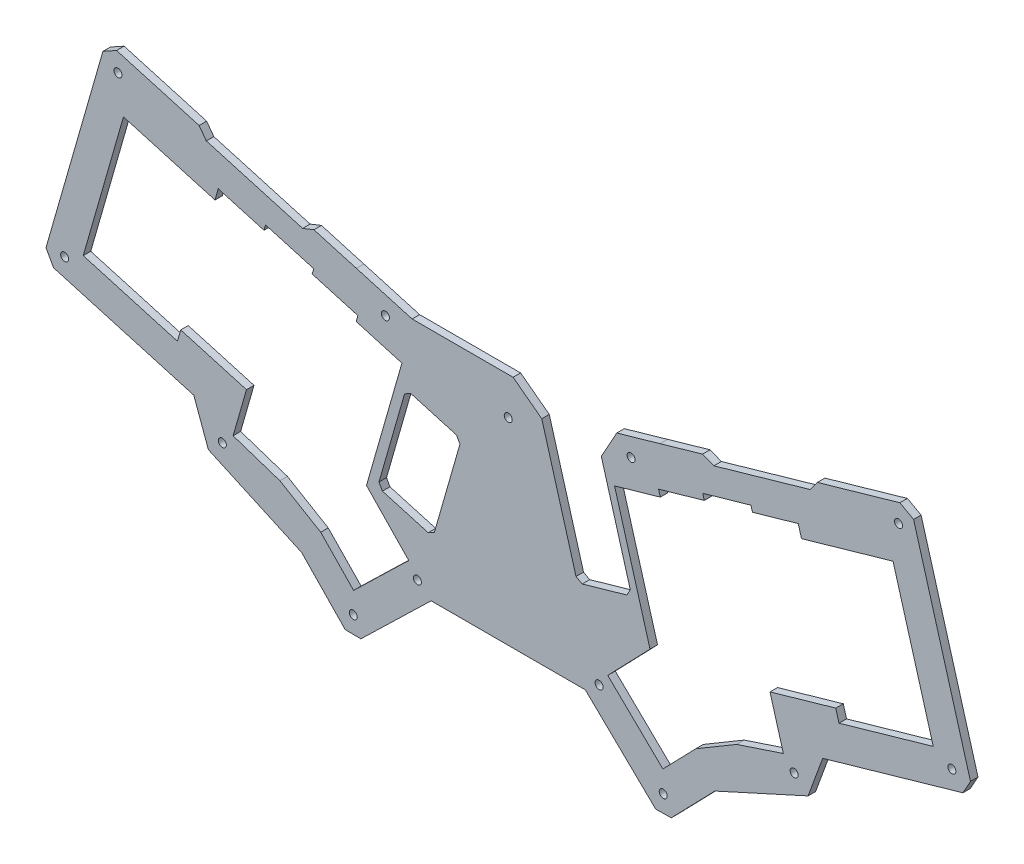
SolidWorks part; units mm, degrees
ref_plane "Plan de face" through (0, 0, 0) normal (0, 0, 1) x (1, 0, 0)
ref_plane "Plan de dessus" through (0, 0, 0) normal (0, 1, 0) x (1, 0, 0)
ref_plane "Plan de droite" through (0, 0, 0) normal (1, 0, 0) x (0, 0, -1)
sketch "Esquisse1" plane through (0, 0, 0) normal (0, 0, 1) x (1, 0, 0)
  line L0 (-121.6461, -32.0475) -> (-108.1875, -28.1884) construction
  line L1 (-108.1875, -28.1884) -> (-104.3283, -41.647) construction
  line L2 (-104.3283, -41.647) -> (-117.7869, -45.5062) construction
  line L3 (-117.7869, -45.5062) -> (-121.6461, -32.0475) construction
  line L4 (-100.1763, -37.9855) -> (-104.0355, -24.5269) construction
  line L5 (-104.0355, -24.5269) -> (-90.5769, -20.6677) construction
  line L6 (-90.5769, -20.6677) -> (-86.7177, -34.1263) construction
  line L7 (-86.7177, -34.1263) -> (-100.1763, -37.9855) construction
  line L8 (-82.5657, -30.4649) -> (-86.4249, -17.0063) construction
  line L9 (-86.4249, -17.0063) -> (-72.9663, -13.1471) construction
  line L10 (-72.9663, -13.1471) -> (-69.1071, -26.6057) construction
  line L11 (-69.1071, -26.6057) -> (-82.5657, -30.4649) construction
  line L12 (-63.6458, -27.5106) -> (-67.505, -14.0519) construction
  line L13 (-67.505, -14.0519) -> (-54.0463, -10.1927) construction
  line L14 (-54.0463, -10.1927) -> (-50.1872, -23.6514) construction
  line L15 (-50.1872, -23.6514) -> (-63.6458, -27.5106) construction
  line L16 (-44.0711, -26.8394) -> (-47.9303, -13.3808) construction
  line L17 (-47.9303, -13.3808) -> (-34.4717, -9.5216) construction
  line L18 (-34.4717, -9.5216) -> (-30.6125, -22.9802) construction
  line L19 (-30.6125, -22.9802) -> (-44.0711, -26.8394) construction
  line L20 (-25.8054, -21.6018) -> (-29.6646, -8.1432) construction
  line L21 (-29.6646, -8.1432) -> (-16.206, -4.284) construction
  line L22 (-16.206, -4.284) -> (-12.3468, -17.7426) construction
  line L23 (-12.3468, -17.7426) -> (-25.8054, -21.6018) construction
  line L24 (-116.4086, -50.3128) -> (-102.95, -46.4536) construction
  line L25 (-102.95, -46.4536) -> (-99.0908, -59.9122) construction
  line L26 (-99.0908, -59.9122) -> (-112.5494, -63.7714) construction
  line L27 (-112.5494, -63.7714) -> (-116.4086, -50.3128) construction
  line L28 (-98.798, -42.7922) -> (-85.3394, -38.933) construction
  line L29 (-85.3394, -38.933) -> (-81.4802, -52.3916) construction
  line L30 (-81.4802, -52.3916) -> (-94.9388, -56.2508) construction
  line L31 (-94.9388, -56.2508) -> (-98.798, -42.7922) construction
  line L32 (-81.1874, -35.2715) -> (-67.7288, -31.4123) construction
  line L33 (-67.7288, -31.4123) -> (-63.8696, -44.8709) construction
  line L34 (-63.8696, -44.8709) -> (-77.3282, -48.7301) construction
  line L35 (-77.3282, -48.7301) -> (-81.1874, -35.2715) construction
  line L36 (-62.2675, -32.3172) -> (-48.8089, -28.458) construction
  line L37 (-48.8089, -28.458) -> (-44.9497, -41.9166) construction
  line L38 (-44.9497, -41.9166) -> (-58.4083, -45.7758) construction
  line L39 (-58.4083, -45.7758) -> (-62.2675, -32.3172) construction
  line L40 (-42.6928, -31.646) -> (-29.2342, -27.7869) construction
  line L41 (-29.2342, -27.7869) -> (-25.375, -41.2455) construction
  line L42 (-25.375, -41.2455) -> (-38.8336, -45.1047) construction
  line L43 (-38.8336, -45.1047) -> (-42.6928, -31.646) construction
  line L44 (-24.4271, -26.4084) -> (-10.9685, -22.5492) construction
  line L45 (-10.9685, -22.5492) -> (-7.1093, -36.0078) construction
  line L46 (-7.1093, -36.0078) -> (-20.5679, -39.867) construction
  line L47 (-20.5679, -39.867) -> (-24.4271, -26.4084) construction
  line L48 (-19.1896, -44.6737) -> (-5.731, -40.8145) construction
  line L49 (-5.731, -40.8145) -> (-1.8718, -54.2731) construction
  line L50 (-1.8718, -54.2731) -> (-15.3304, -58.1323) construction
  line L51 (-15.3304, -58.1323) -> (-19.1896, -44.6737) construction
  line L52 (-37.4554, -49.9113) -> (-23.9967, -46.0521) construction
  line L53 (-23.9967, -46.0521) -> (-20.1376, -59.5107) construction
  line L54 (-20.1376, -59.5107) -> (-33.5962, -63.3699) construction
  line L55 (-33.5962, -63.3699) -> (-37.4554, -49.9113) construction
  line L56 (-57.03, -50.5825) -> (-43.5714, -46.7233) construction
  line L57 (-43.5714, -46.7233) -> (-39.7122, -60.1819) construction
  line L58 (-39.7122, -60.1819) -> (-53.1708, -64.0411) construction
  line L59 (-53.1708, -64.0411) -> (-57.03, -50.5825) construction
  line L60 (-75.9499, -53.5368) -> (-62.4913, -49.6776) construction
  line L61 (-62.4913, -49.6776) -> (-58.6321, -63.1362) construction
  line L62 (-58.6321, -63.1362) -> (-72.0908, -66.9954) construction
  line L63 (-72.0908, -66.9954) -> (-75.9499, -53.5368) construction
  line L64 (-93.5605, -61.0574) -> (-80.1019, -57.1982) construction
  line L65 (-80.1019, -57.1982) -> (-76.2427, -70.6569) construction
  line L66 (-76.2427, -70.6569) -> (-89.7013, -74.516) construction
  line L67 (-89.7013, -74.516) -> (-93.5605, -61.0574) construction
  line L68 (-111.1711, -68.5781) -> (-97.7125, -64.7189) construction
  line L69 (-97.7125, -64.7189) -> (-93.8533, -78.1775) construction
  line L70 (-93.8533, -78.1775) -> (-107.3119, -82.0367) construction
  line L71 (-107.3119, -82.0367) -> (-111.1711, -68.5781) construction
  line L72 (-79.0181, -77.3048) -> (-65.5595, -73.4456) construction
  line L73 (-65.5595, -73.4456) -> (-61.7003, -86.9042) construction
  line L74 (-61.7003, -86.9042) -> (-75.1589, -90.7634) construction
  line L75 (-75.1589, -90.7634) -> (-79.0181, -77.3048) construction
  line L76 (-99.4001, -88.1351) -> (-87.3916, -80.9362) construction
  line L77 (-87.3916, -80.9362) -> (-80.1927, -92.9448) construction
  line L78 (-80.1927, -92.9448) -> (-92.2012, -100.1436) construction
  line L79 (-92.2012, -100.1436) -> (-99.4001, -88.1351) construction
  line L80 (-120.0498, -100.4367) -> (-110.317, -90.3719) construction
  line L81 (-110.317, -90.3719) -> (-100.2522, -100.1047) construction
  line L82 (-100.2522, -100.1047) -> (-109.985, -110.1695) construction
  line L83 (-109.985, -110.1695) -> (-120.0498, -100.4367) construction
  line L86 (0.634, -55.7756) -> (-52.9527, -71.1413) construction
  line L89 (-59.2205, -88.2424) -> (-52.9527, -71.1413) construction
  line L96 (-93.4066, -103.0586) -> (-59.4637, -88.3612) construction
  line L97 (-105.418, -115.2057) -> (-93.9754, -103.3509) construction
  line L98 (-126.5332, -96.9919) -> (-107.5003, -115.385) construction
  line L99 (-167.7972, -50.1766) -> (-183.2082, -64.014) construction
  line L100 (-106.3822, -25.4572) -> (-123.6848, -30.4187) construction
  line L101 (-72.1178, -10.6906) -> (-88.4663, -15.3784) construction
  line L102 (-53.2337, -7.6163) -> (-70.5393, -12.5786) construction
  line L103 (-33.6604, -6.9452) -> (-50.9661, -11.9075) construction
  line L104 (-15.3965, -1.7081) -> (-31.745, -6.396) construction
  line L105 (0.5403, -55.2132) -> (-14.6896, -2.0999) construction
  line L106 (-16.199, -60.6113) -> (0.1495, -55.9235) construction
  line L107 (-52.7198, -71.0835) -> (-18.1144, -61.1606) construction
  line L108 (-59.1184, -88.0534) -> (-52.9674, -71.2752) construction
  line L109 (-183.2082, -64.014) -> (-173.1824, -64.9357) construction
  line L113 (-102.2678, -134.438) -> (-84.7238, -116.3191) construction
  line L114 (-84.7238, -116.3191) -> (-47.2969, -99.2981) construction
  line L115 (-47.2969, -99.2981) -> (-41.4917, -83.4594) construction
  line L116 (14.3812, -67.4381) -> (-41.4917, -83.4594) construction
  line L117 (17.8093, -61.2536) -> (-5.1371, 18.7701) construction
  line L122 (-11.3217, 22.1985) -> (-107.4545, -5.3614) construction
  line L129 (-167.7953, -27.6055) -> (-167.7953, -64.7189) construction
  line L130 (-242.0685, -103.8419) -> (-276.37, -88.2424) construction
  line L131 (-229.5108, -116.8112) -> (-242.0685, -103.8419) construction
  line L138 (-208.9328, -96.8551) -> (-229.5108, -116.8112) construction
  line L139 (-225.5107, -79.6567) -> (-208.9328, -96.8551) construction
  line L140 (-109.3352, -134.5492) -> (-102.2678, -134.438) construction
  line L142 (-5.1371, 18.7701) -> (-11.3217, 22.1985) construction
  line L143 (-211.4691, -30.6868) -> (-225.5107, -79.6567) construction
  line L147 (-114.18, -7.2899) -> (-107.4545, -5.3614) construction
  line L148 (-114.18, -7.2899) -> (-123.7936, -10.0465) construction
  line L154 (-118.7579, -16.9241) -> (-12.0005, 13.6817) construction
  line L155 (-131.531, -101.8802) -> (-105.9239, -126.7133) construction
  line L156 (-105.9239, -126.7133) -> (-89.4162, -109.6646) construction
  line L157 (-128.0696, -96.8789) -> (-106.0575, -118.2258)
  line L158 (-106.0575, -118.2258) -> (-92.9354, -104.6737)
  line L159 (-92.9354, -104.6737) -> (-58.4256, -88.9794) construction
  line L161 (1.8709, -56.4612) -> (-35.7408, -67.2462)
  line L162 (1.8709, -56.4612) -> (-14.1861, -0.4639)
  line L163 (-14.1861, -0.4639) -> (-50.7166, -10.9388)
  line L164 (-50.7166, -10.9388) -> (-52.026, -6.3725)
  line L165 (-52.026, -6.3725) -> (-70.2913, -11.61)
  line L166 (-70.2913, -11.61) -> (-70.911, -9.4488)
  line L167 (-70.911, -9.4488) -> (-90.1377, -14.9608)
  line L168 (-90.1377, -14.9608) -> (-89.5177, -17.1231)
  line L169 (-89.5177, -17.1231) -> (-107.783, -22.3606)
  line L170 (-107.783, -22.3606) -> (-107.0938, -24.7639)
  line L171 (-107.0938, -24.7639) -> (-125.3583, -30.0011)
  line L172 (-125.3583, -30.0011) -> (-111.2001, -79.378)
  line L173 (-111.2001, -79.378) -> (-127.3777, -96.1611)
  line L174 (-89.4162, -109.6646) -> (-53.6562, -93.4017) construction
  line L175 (-53.6562, -93.4017) -> (-47.6042, -76.8897) construction
  line L176 (9.2923, -60.5749) -> (-47.6042, -76.8897) construction
  line L177 (9.2923, -60.5749) -> (-12.0005, 13.6817) construction
  line L178 (-229.7336, -25.4495) -> (-211.4691, -30.6868) construction
  line L179 (-229.0444, -23.0462) -> (-229.7336, -25.4495) construction
  line L180 (-173.1824, -64.9357) -> (-167.7972, -60.1004) construction
  line L181 (-247.3097, -17.8087) -> (-229.0444, -23.0462) construction
  line L185 (17.8093, -61.2536) -> (14.3812, -67.4381) construction
  line L186 (-183.2987, -65.7677) -> (-173.2729, -66.6895) construction
  line L187 (-173.2729, -66.6895) -> (-167.8052, -74.7882) construction
  line L190 (-246.6897, -15.6465) -> (-247.3097, -17.8087) construction
  line L191 (-263.9939, -10.6857) -> (-246.6897, -15.6465) construction
  line L192 (-264.6136, -12.8469) -> (-263.9939, -10.6857) construction
  line L193 (-282.8789, -7.6094) -> (-264.6136, -12.8469) construction
  line L194 (-284.1883, -12.1757) -> (-282.8789, -7.6094) construction
  line L195 (-320.7188, -1.7008) -> (-284.1883, -12.1757) construction
  line L196 (-336.2245, -55.7756) -> (-320.7188, -1.7008) construction
  line L197 (-183.2987, -65.7677) -> (-167.8052, -88.0782) construction
  line L198 (-181.8414, -71.5322) -> (-174.8684, -81.0171) construction
  line L199 (-174.8684, -81.0171) -> (-178.3549, -83.9622) construction
  line L200 (-344.8828, -60.5749) -> (-323.5901, 13.6817) construction
  line L201 (-344.8828, -60.5749) -> (-287.9863, -76.8897) construction
  line L202 (-281.9343, -93.4017) -> (-287.9863, -76.8897) construction
  line L203 (-246.1743, -109.6646) -> (-281.9343, -93.4017) construction
  line L204 (-224.3904, -79.378) -> (-208.2128, -96.1611)
  line L205 (-210.2322, -30.0011) -> (-224.3904, -79.378)
  line L206 (-228.4967, -24.7639) -> (-210.2322, -30.0011)
  line L207 (-227.8075, -22.3606) -> (-228.4967, -24.7639)
  line L208 (-246.0728, -17.1231) -> (-227.8075, -22.3606)
  line L209 (-245.4528, -14.9608) -> (-246.0728, -17.1231)
  line L210 (-264.6796, -9.4488) -> (-245.4528, -14.9608)
  line L211 (-265.2993, -11.61) -> (-264.6796, -9.4488)
  line L212 (-283.5645, -6.3725) -> (-265.2993, -11.61)
  line L213 (-284.8739, -10.9388) -> (-283.5645, -6.3725)
  line L217 (0.634, -55.7756) -> (-14.8717, -1.7008) construction
  line L220 (-14.8717, -1.7008) -> (-51.4022, -12.1757) construction
  line L221 (-51.4022, -12.1757) -> (-52.7116, -7.6094) construction
  line L222 (-52.7116, -7.6094) -> (-70.9769, -12.8469) construction
  line L223 (-70.9769, -12.8469) -> (-71.5966, -10.6857) construction
  line L224 (-71.5966, -10.6857) -> (-88.9008, -15.6465) construction
  line L225 (-88.9008, -15.6465) -> (-88.2808, -17.8087) construction
  line L226 (-88.2808, -17.8087) -> (-106.5461, -23.0462) construction
  line L227 (-106.5461, -23.0462) -> (-105.8569, -25.4495) construction
  line L228 (-105.8569, -25.4495) -> (-124.1214, -30.6868) construction
  line L231 (-124.1214, -30.6868) -> (-110.0799, -79.6567) construction
  line L232 (-110.0799, -79.6567) -> (-126.6577, -96.8551) construction
  line L233 (-126.6577, -96.8551) -> (-106.0797, -116.8112) construction
  line L234 (-106.0797, -116.8112) -> (-93.522, -103.8419) construction
  line L235 (-93.522, -103.8419) -> (-59.2205, -88.2424) construction
  line L236 (-321.4044, -0.4639) -> (-284.8739, -10.9388)
  line L237 (-337.4614, -56.4612) -> (-321.4044, -0.4639)
  line L238 (-337.4614, -56.4612) -> (-299.8497, -67.2462)
  line L241 (-229.5331, -118.2258) -> (-242.6551, -104.6737)
  line L242 (-208.2366, -97.573) -> (-229.5331, -118.2258)
  line L243 (-229.6666, -126.7133) -> (-246.1743, -109.6646) construction
  line L244 (-204.0596, -101.8802) -> (-229.6666, -126.7133) construction
  line L245 (-331.2803, 15.8863) -> (-193.4471, -23.6284) construction
  line L246 (-178.3549, -83.9622) -> (-185.8788, -75.0552) construction
  line L247 (-185.8788, -75.0552) -> (-181.8414, -71.5322) construction
  line L248 (-176.7625, -46.6332) -> (-185.5498, -54.5291) construction
  line L249 (-185.5498, -54.5291) -> (-181.1562, -59.4188) construction
  line L250 (-181.1562, -59.4188) -> (-172.3689, -51.5229) construction
  line L251 (-276.4721, -88.0534) -> (-282.6232, -71.2752) construction
  line L252 (-282.8707, -71.0835) -> (-317.4761, -61.1606) construction
  line L253 (-319.3915, -60.6113) -> (-335.74, -55.9235) construction
  line L254 (-336.1309, -55.2132) -> (-320.9009, -2.0999) construction
  line L255 (-320.194, -1.7081) -> (-303.8455, -6.396) construction
  line L256 (-301.9301, -6.9452) -> (-284.6245, -11.9075) construction
  line L257 (-282.3568, -7.6163) -> (-265.0512, -12.5786) construction
  line L258 (-263.4727, -10.6906) -> (-247.1242, -15.3784) construction
  line L259 (-229.2083, -25.4572) -> (-211.9057, -30.4187) construction
  line L260 (-172.3689, -51.5229) -> (-176.7625, -46.6332) construction
  line L261 (-209.0573, -96.9919) -> (-228.0902, -115.385) construction
  line L262 (-230.1725, -115.2057) -> (-241.6151, -103.3509) construction
  line L263 (-242.1839, -103.0586) -> (-276.1268, -88.3612) construction
  line L264 (-276.37, -88.2424) -> (-282.6379, -71.1413) construction
  line L265 (-336.2245, -55.7756) -> (-282.6379, -71.1413) construction
  line L268 (-353.3998, -61.2536) -> (-349.9717, -67.4381) construction
  line L274 (-221.4105, -7.2899) -> (-206.0252, -11.7015) construction
  line L275 (-221.4105, -7.2899) -> (-228.136, -5.3614) construction
  line L276 (-330.4534, 18.7701) -> (-324.2688, 22.1985) construction
  line L277 (-226.2553, -134.5492) -> (-233.3227, -134.438) construction
  line L281 (-324.2688, 22.1985) -> (-228.136, -5.3614) construction
  line L282 (-353.3998, -61.2536) -> (-330.4534, 18.7701) construction
  line L283 (-349.9717, -67.4381) -> (-294.0988, -83.4594) construction
  line L284 (-288.2936, -99.2981) -> (-294.0988, -83.4594) construction
  line L285 (-250.8667, -116.3191) -> (-288.2936, -99.2981) construction
  line L286 (-233.3227, -134.438) -> (-250.8667, -116.3191) construction
  line L288 (-225.6055, -110.1695) -> (-215.5407, -100.4367) construction
  line L289 (-235.3383, -100.1047) -> (-225.6055, -110.1695) construction
  line L290 (-225.2735, -90.3719) -> (-235.3383, -100.1047) construction
  line L291 (-215.5407, -100.4367) -> (-225.2735, -90.3719) construction
  line L292 (-243.3893, -100.1436) -> (-236.1904, -88.1351) construction
  line L293 (-255.3978, -92.9448) -> (-243.3893, -100.1436) construction
  line L294 (-248.1989, -80.9362) -> (-255.3978, -92.9448) construction
  line L295 (-236.1904, -88.1351) -> (-248.1989, -80.9362) construction
  line L296 (-260.4316, -90.7634) -> (-256.5724, -77.3048) construction
  line L297 (-273.8902, -86.9042) -> (-260.4316, -90.7634) construction
  line L298 (-270.031, -73.4456) -> (-273.8902, -86.9042) construction
  line L299 (-256.5724, -77.3048) -> (-270.031, -73.4456) construction
  line L300 (-228.2786, -82.0367) -> (-224.4194, -68.5781) construction
  line L301 (-241.7372, -78.1775) -> (-228.2786, -82.0367) construction
  line L302 (-237.878, -64.7189) -> (-241.7372, -78.1775) construction
  line L303 (-224.4194, -68.5781) -> (-237.878, -64.7189) construction
  line L304 (-245.8892, -74.516) -> (-242.03, -61.0574) construction
  line L305 (-259.3478, -70.6569) -> (-245.8892, -74.516) construction
  line L306 (-255.4886, -57.1982) -> (-259.3478, -70.6569) construction
  line L307 (-242.03, -61.0574) -> (-255.4886, -57.1982) construction
  line L308 (-263.4998, -66.9954) -> (-259.6406, -53.5368) construction
  line L309 (-276.9584, -63.1362) -> (-263.4998, -66.9954) construction
  line L310 (-273.0992, -49.6776) -> (-276.9584, -63.1362) construction
  line L311 (-259.6406, -53.5368) -> (-273.0992, -49.6776) construction
  line L312 (-282.4197, -64.0411) -> (-278.5605, -50.5825) construction
  line L313 (-295.8783, -60.1819) -> (-282.4197, -64.0411) construction
  line L314 (-292.0191, -46.7233) -> (-295.8783, -60.1819) construction
  line L315 (-278.5605, -50.5825) -> (-292.0191, -46.7233) construction
  line L316 (-301.9944, -63.3699) -> (-298.1352, -49.9113) construction
  line L317 (-315.453, -59.5107) -> (-301.9944, -63.3699) construction
  line L318 (-311.5938, -46.0521) -> (-315.453, -59.5107) construction
  line L319 (-298.1352, -49.9113) -> (-311.5938, -46.0521) construction
  line L320 (-320.2601, -58.1323) -> (-316.4009, -44.6737) construction
  line L321 (-333.7187, -54.2731) -> (-320.2601, -58.1323) construction
  line L322 (-329.8595, -40.8145) -> (-333.7187, -54.2731) construction
  line L323 (-316.4009, -44.6737) -> (-329.8595, -40.8145) construction
  line L324 (-315.0226, -39.867) -> (-311.1634, -26.4084) construction
  line L325 (-328.4812, -36.0078) -> (-315.0226, -39.867) construction
  line L326 (-324.622, -22.5492) -> (-328.4812, -36.0078) construction
  line L327 (-311.1634, -26.4084) -> (-324.622, -22.5492) construction
  line L328 (-296.7569, -45.1047) -> (-292.8977, -31.646) construction
  line L329 (-310.2155, -41.2455) -> (-296.7569, -45.1047) construction
  line L330 (-306.3563, -27.7869) -> (-310.2155, -41.2455) construction
  line L331 (-292.8977, -31.646) -> (-306.3563, -27.7869) construction
  line L332 (-277.1822, -45.7758) -> (-273.323, -32.3172) construction
  line L333 (-290.6408, -41.9166) -> (-277.1822, -45.7758) construction
  line L334 (-286.7817, -28.458) -> (-290.6408, -41.9166) construction
  line L335 (-273.323, -32.3172) -> (-286.7817, -28.458) construction
  line L336 (-258.2623, -48.7301) -> (-254.4031, -35.2715) construction
  line L337 (-271.7209, -44.8709) -> (-258.2623, -48.7301) construction
  line L338 (-267.8617, -31.4123) -> (-271.7209, -44.8709) construction
  line L339 (-254.4031, -35.2715) -> (-267.8617, -31.4123) construction
  line L340 (-240.6517, -56.2508) -> (-236.7925, -42.7922) construction
  line L341 (-254.1103, -52.3916) -> (-240.6517, -56.2508) construction
  line L342 (-250.2511, -38.933) -> (-254.1103, -52.3916) construction
  line L343 (-236.7925, -42.7922) -> (-250.2511, -38.933) construction
  line L344 (-223.0411, -63.7714) -> (-219.1819, -50.3128) construction
  line L345 (-236.4997, -59.9122) -> (-223.0411, -63.7714) construction
  line L346 (-232.6405, -46.4536) -> (-236.4997, -59.9122) construction
  line L347 (-219.1819, -50.3128) -> (-232.6405, -46.4536) construction
  line L348 (-323.2438, -17.7426) -> (-309.7851, -21.6018) construction
  line L349 (-319.3846, -4.284) -> (-323.2438, -17.7426) construction
  line L350 (-305.926, -8.1432) -> (-319.3846, -4.284) construction
  line L351 (-309.7851, -21.6018) -> (-305.926, -8.1432) construction
  line L352 (-304.978, -22.9802) -> (-291.5194, -26.8394) construction
  line L353 (-301.1188, -9.5216) -> (-304.978, -22.9802) construction
  line L354 (-287.6602, -13.3808) -> (-301.1188, -9.5216) construction
  line L355 (-291.5194, -26.8394) -> (-287.6602, -13.3808) construction
  line L356 (-285.4034, -23.6514) -> (-271.9448, -27.5106) construction
  line L357 (-281.5442, -10.1927) -> (-285.4034, -23.6514) construction
  line L358 (-268.0856, -14.0519) -> (-281.5442, -10.1927) construction
  line L359 (-271.9448, -27.5106) -> (-268.0856, -14.0519) construction
  line L360 (-266.4834, -26.6057) -> (-253.0248, -30.4649) construction
  line L361 (-262.6242, -13.1471) -> (-266.4834, -26.6057) construction
  line L362 (-249.1656, -17.0063) -> (-262.6242, -13.1471) construction
  line L363 (-253.0248, -30.4649) -> (-249.1656, -17.0063) construction
  line L364 (-248.8728, -34.1263) -> (-235.4142, -37.9855) construction
  line L365 (-245.0136, -20.6677) -> (-248.8728, -34.1263) construction
  line L366 (-231.555, -24.5269) -> (-245.0136, -20.6677) construction
  line L367 (-235.4142, -37.9855) -> (-231.555, -24.5269) construction
  line L368 (-217.8036, -45.5062) -> (-213.9444, -32.0475) construction
  line L369 (-231.2622, -41.647) -> (-217.8036, -45.5062) construction
  line L370 (-227.4031, -28.1884) -> (-231.2622, -41.647) construction
  line L371 (-213.9444, -32.0475) -> (-227.4031, -28.1884) construction
  line L372 (-226.2553, -134.5492) -> (-194.0347, -103.3509) construction
  line L373 (-109.3352, -134.5492) -> (-141.5559, -103.3509) construction
  line L374 (-141.5559, -103.3509) -> (-194.0347, -103.3509) construction
  line L375 (-167.7972, -50.1766) -> (-152.3861, -64.014) construction
  line L376 (-162.4119, -64.9357) -> (-167.7972, -60.1004) construction
  line L377 (-162.3376, -66.6895) -> (-167.8052, -74.7882) construction
  line L378 (-152.3118, -65.7677) -> (-167.8052, -88.0782) construction
  line L379 (-163.2254, -51.5229) -> (-158.8318, -46.6332) construction
  line L380 (-154.4381, -59.4188) -> (-163.2254, -51.5229) construction
  line L381 (-150.0445, -54.5291) -> (-154.4381, -59.4188) construction
  line L382 (-158.8318, -46.6332) -> (-150.0445, -54.5291) construction
  line L383 (-149.7316, -75.0552) -> (-153.7691, -71.5322) construction
  line L384 (-157.2555, -83.9622) -> (-149.7316, -75.0552) construction
  line L385 (-160.742, -81.0171) -> (-157.2555, -83.9622) construction
  line L386 (-153.7691, -71.5322) -> (-160.742, -81.0171) construction
  line L387 (-152.3118, -65.7677) -> (-162.3376, -66.6895) construction
  line L388 (-152.3861, -64.014) -> (-162.4119, -64.9357) construction
  line L389 (-206.0252, -11.7015) -> (-129.5654, -11.7015) construction
  line L390 (-119.0708, -62.7964) -> (-130.6498, -22.4155)
  line L391 (-123.5545, -47.16) -> (-127.4136, -33.7014) construction
  line L392 (-120.442, -65.2702) -> (-138.2688, -70.3819)
  line L393 (-140.7426, -69.0107) -> (-154.4194, -21.3141)
  line L394 (-167.1758, -11.7015) -> (-206.0252, -11.7015) construction
  line L395 (-154.4194, -21.3141) -> (-167.1758, -11.7015) construction
  line L396 (-123.7936, -10.0465) -> (-130.6498, -22.4155) construction
  line L397 (-138.2688, -70.3819) -> (-140.7426, -69.0107)
  line L398 (-119.0708, -62.7964) -> (-120.442, -65.2702)
  line L399 (-129.5654, -11.7015) -> (-123.7936, -10.0465) construction
  line L400 (-165.8487, -12.7015) -> (-206.1657, -12.7015)
  line L401 (-221.6861, -8.2511) -> (-206.1657, -12.7015)
  line L402 (-221.6861, -8.2511) -> (-228.4116, -6.3226)
  line L403 (-324.1462, 21.1231) -> (-291.1905, 11.6751)
  line L404 (-329.6063, 18.0963) -> (-324.1462, 21.1231)
  line L405 (-352.3244, -61.1311) -> (-329.6063, 18.0963)
  line L406 (-352.3244, -61.1311) -> (-349.2979, -66.591)
  line L407 (-349.2979, -66.591) -> (-293.3347, -82.6382)
  line L408 (-287.4987, -98.561) -> (-293.3347, -82.6382)
  line L409 (-250.2802, -115.4872) -> (-287.4987, -98.561)
  line L410 (-232.8926, -133.4446) -> (-250.2802, -115.4872)
  line L411 (-226.6535, -133.5428) -> (-232.8926, -133.4446)
  line L412 (-226.6535, -133.5428) -> (-198.5705, -106.3509)
  line L413 (-141.1511, -102.3509) -> (-194.4395, -102.3509) construction
  line L414 (-108.937, -133.5428) -> (-137.02, -106.3509)
  line L415 (-108.937, -133.5428) -> (-102.6979, -133.4446)
  line L416 (-102.6979, -133.4446) -> (-85.3104, -115.4872)
  line L417 (-85.3104, -115.4872) -> (-48.0918, -98.561)
  line L418 (-48.0918, -98.561) -> (-42.2558, -82.6382)
  line L419 (13.7074, -66.591) -> (-42.2558, -82.6382)
  line L420 (16.7339, -61.1311) -> (13.7074, -66.591)
  line L421 (16.7339, -61.1311) -> (-5.9842, 18.0963)
  line L422 (-5.9842, 18.0963) -> (-11.4443, 21.1231)
  line L423 (-11.4443, 21.1231) -> (-44.4001, 11.6751)
  line L424 (-113.9044, -8.2511) -> (-107.1789, -6.3226)
  line L425 (-113.9044, -8.2511) -> (-124.4792, -11.2834)
  line L426 (-167.1758, -12.7015) -> (-206.1657, -12.7015) construction
  line L427 (-113.9044, -8.2511) -> (-123.5179, -11.0078) construction
  line L428 (-165.8487, -12.7015) -> (-154.4194, -21.3141)
  line L429 (-130.6498, -22.4155) -> (-124.4792, -11.2834)
  line L430 (-208.2366, -97.573) -> (-207.4919, -96.8551)
  line L431 (-207.4919, -96.8551) -> (-208.2128, -96.1611)
  line L432 (-127.3777, -96.1611) -> (-128.0696, -96.8789)
  line L433 (-132.8889, -110.3509) -> (-202.7016, -110.3509) construction
  line L434 (-141.1511, -110.3509) -> (-194.4395, -110.3509) construction
  line L435 (-87.3916, -80.9362) -> (-92.2012, -100.1436) construction
  line L436 (-226.6535, -133.5428) -> (-194.4395, -102.3509) construction
  line L437 (-108.937, -133.5428) -> (-141.1511, -102.3509) construction
  line L438 (-65.5595, -73.4456) -> (-75.1589, -90.7634) construction
  line L439 (-59.5038, -49.2112) -> (-42.2001, -44.2495) construction
  line L440 (-92.8883, -102.8873) -> (-102.1438, -87.448) construction
  line L441 (-102.1438, -87.448) -> (-86.7045, -78.1925) construction
  line L442 (-86.7045, -78.1925) -> (-77.449, -93.6318) construction
  line L443 (-77.449, -93.6318) -> (-92.8883, -102.8873) construction
  line L444 (-76.5302, -93.2372) -> (-81.4919, -75.9335) construction
  line L445 (-81.4919, -75.9335) -> (-64.1883, -70.9718) construction
  line L446 (-64.1883, -70.9718) -> (-59.2265, -88.2755) construction
  line L447 (-59.2265, -88.2755) -> (-76.5302, -93.2372) construction
  line L448 (-42.2001, -44.2495) -> (-37.2384, -61.5531) construction
  line L449 (-37.2384, -61.5531) -> (-54.5421, -66.5149) construction
  line L450 (-54.5421, -66.5149) -> (-59.5038, -49.2112) construction
  line L451 (-76.6212, -95.0127) -> (-92.0605, -104.2682) construction
  line L452 (-92.9354, -104.6737) -> (-76.6212, -95.0127)
  line L453 (-76.6212, -95.0127) -> (-57.9612, -88.8254)
  line L454 (-39.9292, -48.5401) -> (-22.6255, -43.5783) construction
  line L455 (-22.6255, -43.5783) -> (-17.6638, -60.882) construction
  line L456 (-17.6638, -60.882) -> (-34.9674, -65.8437) construction
  line L457 (-34.9674, -65.8437) -> (-39.9292, -48.5401) construction
  line L458 (-63.102, -70.6603) -> (-58.1403, -87.964) construction
  line L459 (-36.9269, -62.6394) -> (-54.2306, -67.6011) construction
  line L460 (-36.0536, -66.1552) -> (-41.0154, -48.8515) construction
  line L461 (-57.9612, -88.8254) -> (-63.3014, -70.2021)
  line L462 (-37.0515, -62.6751) -> (-63.3014, -70.2021)
  line L463 (-37.0515, -62.6751) -> (-35.7408, -67.2462)
  line L464 (-298.539, -62.6751) -> (-299.8497, -67.2462)
  line L465 (-298.539, -62.6751) -> (-272.2891, -70.2021)
  line L466 (-277.6293, -88.8254) -> (-272.2891, -70.2021)
  line L467 (-258.9693, -95.0127) -> (-277.6293, -88.8254)
  line L468 (-242.6551, -104.6737) -> (-258.9693, -95.0127)
  line L469 (-98.0641, -3.7095) -> (-90.2165, -1.4597)
  line L470 (-94.657, -1.6925) -> (-56.2059, 9.3309) construction
  line L471 (-94.657, -1.6925) -> (-56.2059, 9.3309) construction
  line L474 (-98.0641, -3.7095) -> (-107.1789, -6.3226)
  line L476 (-11.4443, 21.1231) -> (-107.1789, -6.3226) construction
  line L481 (-237.5264, -3.7095) -> (-228.4116, -6.3226)
  line L482 (-66.4927, 2.2629) -> (-65.3792, -1.6212) construction
  line L483 (-324.1462, 21.1231) -> (-228.4116, -6.3226) construction
  line L484 (-85.7183, -3.2488) -> (-47.2672, 7.7746)
  line L485 (-90.2165, -1.4597) -> (-85.7183, -3.2488)
  line L486 (-44.4001, 11.6751) -> (-47.2672, 7.7746)
  line L487 (-291.1905, 11.6751) -> (-288.3233, 7.7746)
  line L488 (-249.8723, -3.2488) -> (-288.3233, 7.7746)
  line L489 (-245.374, -1.4597) -> (-249.8723, -3.2488)
  line L490 (-245.374, -1.4597) -> (-237.5264, -3.7095)
  line L491 (-134.9544, -108.3509) -> (-200.6361, -108.3509) construction
  line L492 (-137.02, -106.3509) -> (-198.5705, -106.3509)
  line L493 (-132.8889, -108.3509) -> (-202.7016, -108.3509) construction
  line L494 (-197.2749, -82.0103) -> (-187.0783, -46.443)
  line L495 (-134.9544, -106.3509) -> (-200.6361, -106.3509) construction
  line L504 (-188.4497, -43.9693) -> (-206.714, -38.7332)
  line L505 (-219.3843, -75.6719) -> (-209.1877, -40.1046)
  line L506 (-199.7487, -83.3817) -> (-218.0129, -78.1456)
  line L507 (-206.714, -38.7332) -> (-209.1877, -40.1046)
  line L508 (-187.0783, -46.443) -> (-188.4497, -43.9693)
  line L509 (-199.7487, -83.3817) -> (-197.2749, -82.0103)
  line L510 (-218.0129, -78.1456) -> (-219.3843, -75.6719)
  line L511 (-192.1766, -64.2267) -> (-167.7953, -64.7189) construction
  circle A2 centre (-12.0005, 13.6817) radius 1.6
  circle A3 centre (-12.0005, 13.6817) radius 3 construction
  circle A4 centre (-118.7579, -16.9241) radius 1.6
  circle A5 centre (9.2923, -60.5749) radius 1.6
  circle A6 centre (-53.6562, -93.4017) radius 1.6
  circle A7 centre (-105.9239, -126.7133) radius 1.6
  circle A8 centre (-131.531, -101.8802) radius 1.6
  circle A10 centre (-147.4897, -45.973) radius 1.6 construction
  circle A11 centre (-323.5901, 13.6817) radius 3 construction
  circle A12 centre (-188.1008, -45.973) radius 1.6 construction
  circle A14 centre (-204.0596, -101.8802) radius 1.6
  circle A15 centre (-229.6666, -126.7133) radius 1.6
  circle A16 centre (-281.9343, -93.4017) radius 1.6
  circle A17 centre (-344.8828, -60.5749) radius 1.6
  circle A18 centre (-216.8326, -16.9241) radius 1.6
  circle A19 centre (-323.5901, 13.6817) radius 1.6
  circle A20 centre (-167.7953, -27.6055) radius 1.6
  point P138 (-167.7953, -27.6055)
  point P139 (-6.5153, 23.5764)
  point P150 (-169.1046, -23.0392)
  point P172 (-65.3792, -1.6212)
  point P200 (19.1875, -66.0599)
  point P203 (-141.5228, -71.3355)
  point P204 (-141.5228, 1.5705)
  point P263 (-133.4062, -12.8029)
  point P264 (-118.5195, -64.7189)
  point P283 (-140.1914, -70.9332)
  point P284 (-157.1758, -11.7015)
  point P405 (-354.778, -66.0599)
  point P406 (-329.0752, 23.5764)
  point P470 (-75.4315, 3.8192)
  point P473 (-75.4315, 3.8192)
  dimension "D3" = 3.2
  dimension "D4" = 6
  dimension "D6" = 3.2
  dimension "D7" = 3.2
  dimension "D8" = 3.2
  dimension "D9" = 3.2
  dimension "D10" = 3.2
  dimension "D16" = 3.2
  dimension "D2" = 6
  dimension "D5" = 1
  dimension "D14" = 2
  dimension "D21" = 1.61
  dimension "D22" = 2
  dimension "D23" = 1.1349
  dimension "D24" = 1.13
  dimension "D27" = 40
  dimension "D28" = 2
  dimension "D11" = 8
  dimension "D18" = 2
  dimension "D20" = 2
  dimension "D25" = 1.13
  dimension "D26" = 1.13
  dimension "D29" = 2
extrude "Boss.-Extru.1" add sketch "Esquisse1" along normal blind 3
sketch "Esquisse2" plane through (0, 0, 3) normal (0, 0, 1) x (1, 0, 0)
  line L0 (-167.7953, -110.3509) -> (-167.7953, -102.3509) construction
  line L1 (-132.8889, -110.3509) -> (-202.7016, -110.3509) construction
  line L2 (-168.7953, -110.3509) -> (-168.7953, -102.3509)
  line L3 (-166.7953, -110.3509) -> (-166.7953, -102.3509)
  line L4 (-163.7953, -110.3509) -> (-163.7953, -102.3509) construction
  line L5 (-164.7953, -110.3509) -> (-164.7953, -102.3509)
  line L6 (-162.7953, -110.3509) -> (-162.7953, -102.3509)
  line L7 (-159.7953, -110.3509) -> (-159.7953, -102.3509) construction
  line L8 (-160.7953, -110.3509) -> (-160.7953, -102.3509)
  line L9 (-158.7953, -110.3509) -> (-158.7953, -102.3509)
  line L10 (-155.7953, -110.3509) -> (-155.7953, -102.3509) construction
  line L11 (-156.7953, -110.3509) -> (-156.7953, -102.3509)
  line L12 (-154.7953, -110.3509) -> (-154.7953, -102.3509)
  line L13 (-151.7953, -110.3509) -> (-151.7953, -102.3509) construction
  line L14 (-152.7953, -110.3509) -> (-152.7953, -102.3509)
  line L15 (-150.7953, -110.3509) -> (-150.7953, -102.3509)
  line L16 (-147.7953, -110.3509) -> (-147.7953, -102.3509) construction
  line L17 (-148.7953, -110.3509) -> (-148.7953, -102.3509)
  line L18 (-146.7953, -110.3509) -> (-146.7953, -102.3509)
  line L19 (-171.7953, -110.3509) -> (-171.7953, -102.3509) construction
  line L20 (-172.7953, -110.3509) -> (-172.7953, -102.3509)
  line L21 (-170.7953, -110.3509) -> (-170.7953, -102.3509)
  line L22 (-175.7953, -110.3509) -> (-175.7953, -102.3509) construction
  line L23 (-176.7953, -110.3509) -> (-176.7953, -102.3509)
  line L24 (-174.7953, -110.3509) -> (-174.7953, -102.3509)
  line L25 (-179.7953, -110.3509) -> (-179.7953, -102.3509) construction
  line L26 (-180.7953, -110.3509) -> (-180.7953, -102.3509)
  line L27 (-178.7953, -110.3509) -> (-178.7953, -102.3509)
  line L28 (-183.7953, -110.3509) -> (-183.7953, -102.3509) construction
  line L29 (-184.7953, -110.3509) -> (-184.7953, -102.3509)
  line L30 (-182.7953, -110.3509) -> (-182.7953, -102.3509)
  line L31 (-187.7953, -110.3509) -> (-187.7953, -102.3509) construction
  line L32 (-188.7953, -110.3509) -> (-188.7953, -102.3509)
  line L33 (-186.7953, -110.3509) -> (-186.7953, -102.3509)
  arc A0 (-168.7953, -110.3509) -> (-166.7953, -110.3509) centre (-167.7953, -110.3509) ccw
  arc A1 (-166.7953, -102.3509) -> (-168.7953, -102.3509) centre (-167.7953, -102.3509) ccw
  arc A2 (-164.7953, -110.3509) -> (-162.7953, -110.3509) centre (-163.7953, -110.3509) ccw
  arc A3 (-162.7953, -102.3509) -> (-164.7953, -102.3509) centre (-163.7953, -102.3509) ccw
  arc A4 (-160.7953, -110.3509) -> (-158.7953, -110.3509) centre (-159.7953, -110.3509) ccw
  arc A5 (-158.7953, -102.3509) -> (-160.7953, -102.3509) centre (-159.7953, -102.3509) ccw
  arc A6 (-156.7953, -110.3509) -> (-154.7953, -110.3509) centre (-155.7953, -110.3509) ccw
  arc A7 (-154.7953, -102.3509) -> (-156.7953, -102.3509) centre (-155.7953, -102.3509) ccw
  arc A8 (-152.7953, -110.3509) -> (-150.7953, -110.3509) centre (-151.7953, -110.3509) ccw
  arc A9 (-150.7953, -102.3509) -> (-152.7953, -102.3509) centre (-151.7953, -102.3509) ccw
  arc A10 (-148.7953, -110.3509) -> (-146.7953, -110.3509) centre (-147.7953, -110.3509) ccw
  arc A11 (-146.7953, -102.3509) -> (-148.7953, -102.3509) centre (-147.7953, -102.3509) ccw
  arc A12 (-172.7953, -110.3509) -> (-170.7953, -110.3509) centre (-171.7953, -110.3509) ccw
  arc A13 (-170.7953, -102.3509) -> (-172.7953, -102.3509) centre (-171.7953, -102.3509) ccw
  arc A14 (-176.7953, -110.3509) -> (-174.7953, -110.3509) centre (-175.7953, -110.3509) ccw
  arc A15 (-174.7953, -102.3509) -> (-176.7953, -102.3509) centre (-175.7953, -102.3509) ccw
  arc A16 (-180.7953, -110.3509) -> (-178.7953, -110.3509) centre (-179.7953, -110.3509) ccw
  arc A17 (-178.7953, -102.3509) -> (-180.7953, -102.3509) centre (-179.7953, -102.3509) ccw
  arc A18 (-184.7953, -110.3509) -> (-182.7953, -110.3509) centre (-183.7953, -110.3509) ccw
  arc A19 (-182.7953, -102.3509) -> (-184.7953, -102.3509) centre (-183.7953, -102.3509) ccw
  arc A20 (-188.7953, -110.3509) -> (-186.7953, -110.3509) centre (-187.7953, -110.3509) ccw
  arc A21 (-186.7953, -102.3509) -> (-188.7953, -102.3509) centre (-187.7953, -102.3509) ccw
  point P4 (-167.7953, -106.3509)
  point P13 (-163.7953, -106.3509)
  point P20 (-159.7953, -106.3509)
  point P27 (-155.7953, -106.3509)
  point P34 (-151.7953, -106.3509)
  point P41 (-147.7953, -106.3509)
  point P47 (-171.7953, -106.3509)
  point P54 (-175.7953, -106.3509)
  point P61 (-179.7953, -106.3509)
  point P68 (-183.7953, -106.3509)
  point P75 (-187.7953, -106.3509)
  dimension "D1" = 6
  dimension "D2" = 6
